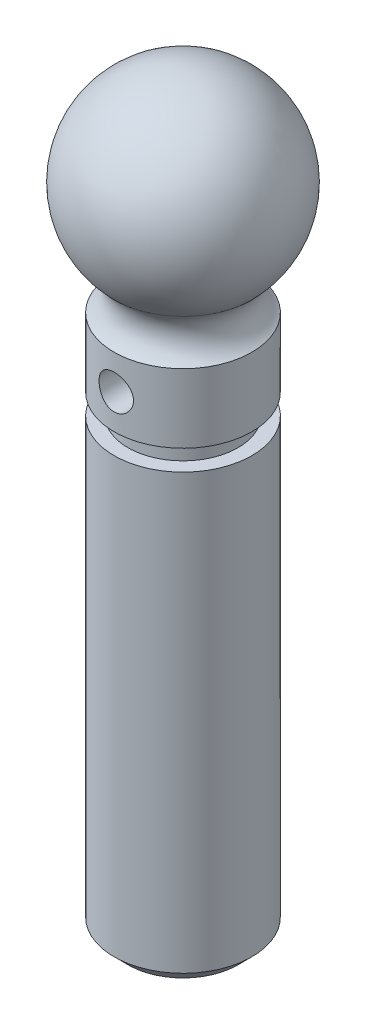
SolidWorks part; units mm, degrees
ref_plane "Plan de face" through (0, 0, 0) normal (0, 0, 1) x (1, 0, 0)
ref_plane "Plan de dessus" through (0, 0, 0) normal (0, 1, 0) x (1, 0, 0)
ref_plane "Plan de droite" through (0, 0, 0) normal (1, 0, 0) x (0, 0, -1)
sketch "Esquisse1" plane through (0, 0, 0) normal (0, 0, 1) x (1, 0, 0)
  line L0 (0, -208.829) -> (0, 834.3032) construction
  line L1 (0, -152.6297) -> (80, -152.6297)
  line L2 (80, -152.6297) -> (100, -132.6297)
  line L3 (100, -132.6297) -> (0, -132.6297)
  line L4 (0, -132.6297) -> (0, -152.6297)
  line L5 (100, -132.6297) -> (100, 497.3703)
  line L6 (100, 497.3703) -> (0, 497.3703)
  line L7 (0, 497.3703) -> (0, -132.6297)
  line L8 (80, 497.3703) -> (80, 527.3703)
  line L9 (80, 527.3703) -> (0, 527.3703)
  line L10 (0, 527.3703) -> (0, 497.3703)
  line L11 (0, 527.3703) -> (0, 627.3703)
  line L12 (0, 627.3703) -> (100, 627.3703)
  line L13 (100, 527.3703) -> (80, 527.3703)
  line L14 (100, 527.3703) -> (100, 627.3703)
  line L15 (0, 693.1369) -> (100, 693.1369)
  line L16 (0, 627.3703) -> (0, 693.1369)
  line L17 (0, -132.6297) -> (100, -132.6297)
  line L18 (0, 931.1165) -> (0, 693.1369)
  line L19 (0, 834.3032) -> (0, 976.2955) construction
  arc A0 (100, 693.1369) -> (100, 627.3703) centre (122.7748, 660.2536) ccw
  arc A1 (100, 693.1369) -> (0, 931.1165) centre (0, 791.1165) ccw
  circle A2 centre (0, 577.3703) radius 25
  point P17 (50, 693.1369)
  point P24 (0, 931.1165)
  dimension "D9" = 80
  dimension "D14" = 280
  dimension "D18" = 50
  dimension "D1" = 80
  dimension "D2" = 45
  dimension "D3" = 680
  dimension "D4" = 80
  dimension "D5" = 100
  dimension "D6" = 100
  dimension "D7" = 30
  dimension "D8" = 100
  dimension "D10" = 1043.1322
  dimension "D11" = 132.6297
  dimension "D12" = 122.7748
  dimension "D13" = 65.7666
  dimension "D15" = 141.9923
  dimension "D16" = 97.9796
  dimension "D17" = 208.829
revolve "Révolution1" add sketch "Esquisse1" angle 360 about L0
sketch "Esquisse2" plane through (0, 0, 0) normal (0, 0, 1) x (1, 0, 0)
  line L0 (100, 527.3703) -> (100, 627.3703) construction
  line L1 (100, 627.3703) -> (-100, 627.3703) construction
  circle A0 centre (0, 577.3703) radius 25
  dimension "D1" = 50
  dimension "D2" = 100
  dimension "D3" = 50
extrude "Enlèv. mat.-Extru.2" cut sketch "Esquisse2" against normal through all both and the other way through all
